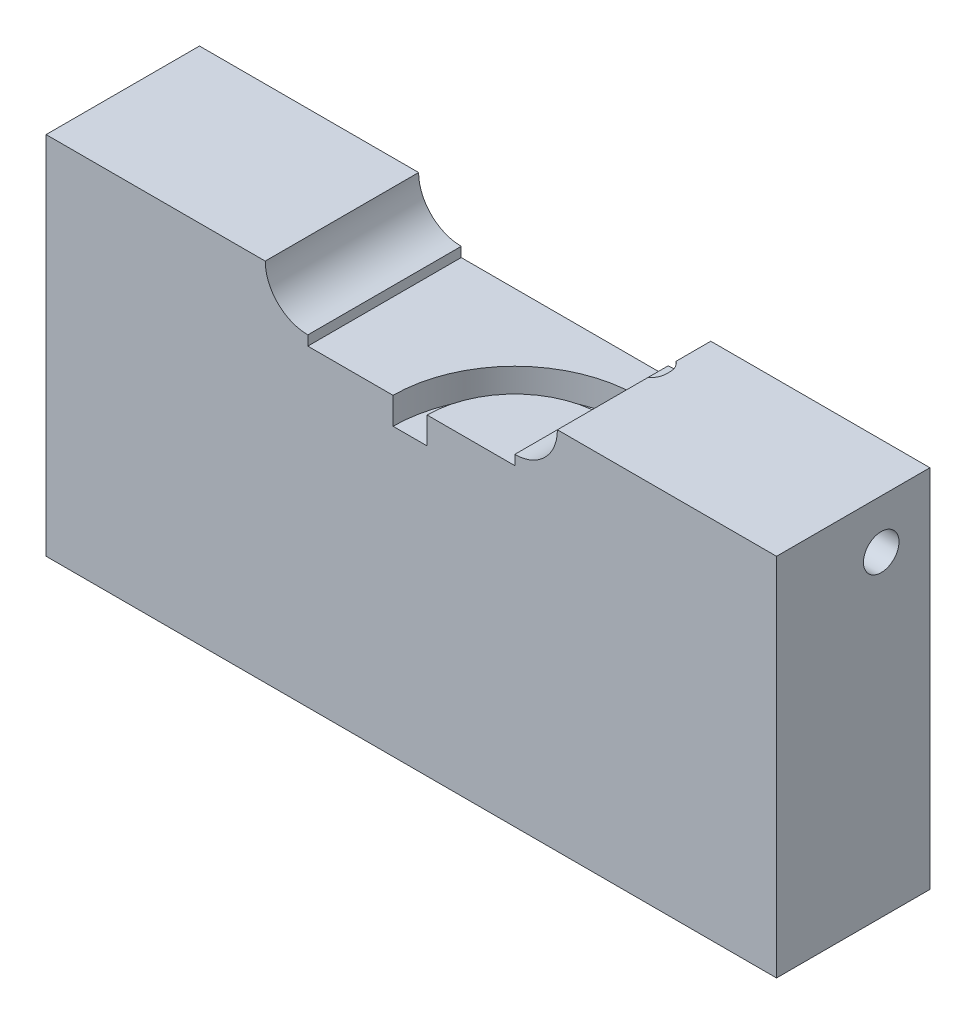
SolidWorks part; units mm, degrees
ref_plane "Front Plane" through (0, 0, 0) normal (0, 0, 1) x (1, 0, 0)
ref_plane "Top Plane" through (0, 0, 0) normal (0, 1, 0) x (1, 0, 0)
ref_plane "Right Plane" through (0, 0, 0) normal (1, 0, 0) x (0, 0, -1)
sketch "Sketch1" plane through (0, 0, 0) normal (0, 1, 0) x (1, 0, 0)
  line L1 (-19.05, -4.0005) -> (19.05, -4.0005)
  line L2 (-19.05, -4.0005) -> (-19.05, 4.0005)
  line L3 (-19.05, 4.0005) -> (19.05, 4.0005)
  line L4 (19.05, -4.0005) -> (19.05, 4.0005)
  line L5 (-19.05, -4.0005) -> (19.05, 4.0005) construction
  line L6 (-19.05, 4.0005) -> (19.05, -4.0005) construction
  point P0 (0, 0)
  dimension "D1" = 38.1
  dimension "D2" = 8.001
extrude "Boss-Extrude1" add sketch "Sketch1" along normal blind 19.05
sketch "Sketch2" plane through (0, 0, -4.0005) normal (0, 0, -1) x (-1, 0, 0)
  line L0 (5.3975, 19.05) -> (-5.3975, 19.05) construction
  line L1 (5.3975, 16.8275) -> (-5.3975, 16.8275)
  line L2 (5.3975, 21.2725) -> (-5.3975, 21.2725)
  line L3 (19.05, 19.05) -> (-19.05, 19.05) construction
  line L4 (-19.05, 0) -> (19.05, 0) construction
  line L6 (19.05, 19.05) -> (19.05, 0) construction
  line L7 (-19.05, 19.05) -> (-19.05, 0) construction
  arc A0 (5.3975, 16.8275) -> (5.3975, 21.2725) centre (5.3975, 19.05) ccw
  arc A1 (-5.3975, 21.2725) -> (-5.3975, 16.8275) centre (-5.3975, 19.05) ccw
  point P2 (0, 19.05)
  dimension "D1" = 19.05
  dimension "D2" = 10.795
  dimension "D3" = 4.445
extrude "Cut-Extrude1" cut sketch "Sketch2" against normal blind 25.4
ref_plane "Plane1" through (0, 16.8275, 0) normal (0, 1, 0) x (1, 0, 0)
sketch "Sketch4" plane through (0, 16.8275, 0) normal (0, 1, 0) x (1, 0, 0)
  line L0 (0, -9.1985) -> (0, 12.0201) construction
  line L1 (0.8255, -4.0005) -> (-0.9525, -4.0005)
  line L2 (5.3975, 0.5715) -> (7.1437, 0.5715)
  line L3 (7.9375, 1.3652) -> (7.9375, 1.5557)
  line L4 (7.1437, 2.3495) -> (5.3975, 2.3495)
  arc A0 (5.3975, 2.3495) -> (-0.9525, -4.0005) centre (5.3975, -4.0005) ccw
  arc A1 (5.3975, 0.5715) -> (0.8255, -4.0005) centre (5.3975, -4.0005) ccw
  arc A2 (7.9375, 1.3652) -> (7.1437, 0.5715) centre (7.1437, 1.3652) cw
  arc A3 (7.9375, 1.5557) -> (7.1437, 2.3495) centre (7.1437, 1.5557) ccw
  dimension "D1" = 12.7
  dimension "D2" = 9.144
  dimension "D3" = 2.54
  dimension "D4" = 0.7937
extrude "Cut-Extrude2" cut sketch "Sketch4" against normal blind 1.905 and the other way through all
ref_plane "Plane3" through (19.05, 0, 0) normal (1, 0, 0) x (0, 0, -1)
sketch "Sketch5" plane through (19.05, 0, 0) normal (1, 0, 0) x (0, 0, -1)
  line L0 (-4.0005, 19.05) -> (-4.0005, 0) construction
  line L1 (-4.0005, 19.05) -> (4.0005, 19.05) construction
  circle A0 centre (1.4605, 16.51) radius 0.9271
  dimension "D2" = 1.8542
  dimension "D1" = 5.461
  dimension "D3" = 2.54
extrude "Cut-Extrude3" cut sketch "Sketch5" against normal blind 12.7
sketch "Sketch6" plane through (0, 16.8275, 0) normal (0, 1, 0) x (1, 0, 0)
  line L1 (-5.3975, 4.0005) -> (5.3975, 4.0005)
  line L2 (-5.3975, 4.0005) -> (-5.3975, -4.0005)
  line L3 (-5.3975, -4.0005) -> (5.3975, -4.0005)
  line L4 (5.3975, 4.0005) -> (5.3975, -4.0005)
extrude "Cut-Extrude4" cut sketch "Sketch6" against normal blind 0.508
